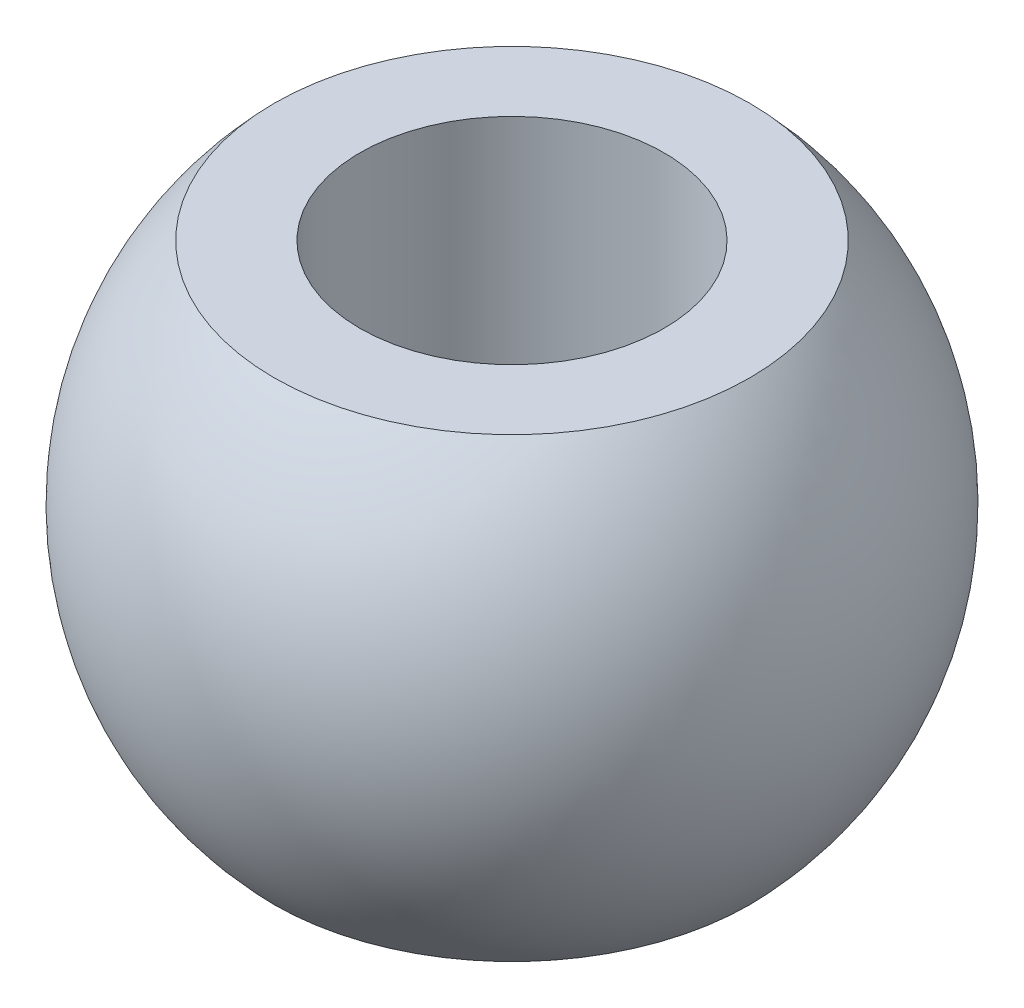
SolidWorks part; units mm, degrees
ref_plane "Front Plane" through (0, 0, 0) normal (0, 0, 1) x (1, 0, 0)
ref_plane "Top Plane" through (0, 0, 0) normal (0, 1, 0) x (1, 0, 0)
ref_plane "Right Plane" through (0, 0, 0) normal (1, 0, 0) x (0, 0, -1)
sketch "Sketch1" plane through (0, 0, 0) normal (0, 0, 1) x (1, 0, 0)
  line L0 (0, 10.054) -> (0, -6.8324) construction
  line L1 (-1.7402, 0) -> (9.7453, 0) construction
  line L2 (1.5, -2.25) -> (2.3452, -2.25)
  line L3 (1.5, -2.25) -> (1.5, 2.25)
  line L4 (1.5, 2.25) -> (2.3452, 2.25)
  arc A0 (2.3452, -2.25) -> (2.3452, 2.25) centre (0, 0) ccw
  point P9 (1.5, 0)
  dimension "D1" = 3.25
  dimension "D2" = 3
  dimension "D3" = 4.5
revolve "Revolve1" add sketch "Sketch1" angle 360 about L0
